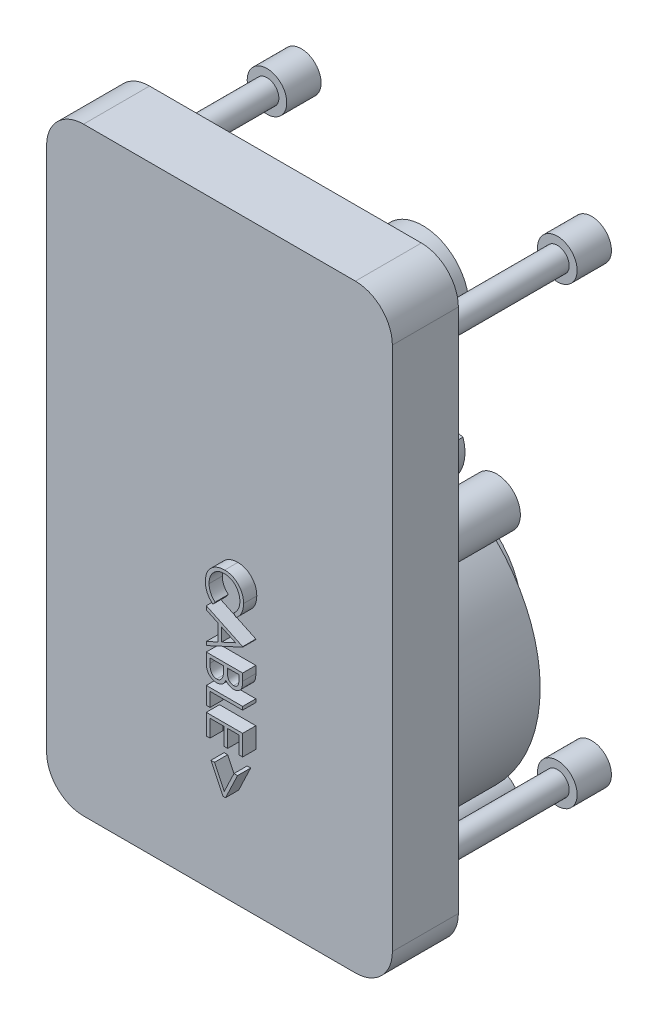
SolidWorks part; units mm, degrees
ref_plane "Front Plane" through (0, 0, 0) normal (0, 0, 1) x (1, 0, 0)
ref_plane "Top Plane" through (0, 0, 0) normal (0, 1, 0) x (1, 0, 0)
ref_plane "Right Plane" through (0, 0, 0) normal (1, 0, 0) x (0, 0, -1)
sketch "Sketch1" plane through (0, 0, 0) normal (0, 0, 1) x (1, 0, 0)
  line L0 (-13.081, 28.829) -> (13.081, 28.829)
  line L1 (-16.637, 25.273) -> (-16.637, -25.273)
  line L2 (-13.081, -28.829) -> (13.081, -28.829)
  line L3 (16.637, 25.273) -> (16.637, -25.273)
  line L4 (-16.637, 28.829) -> (16.637, -28.829) construction
  line L5 (-16.637, -28.829) -> (16.637, 28.829) construction
  line L6 (0, 36.9388) -> (0, -36.9388) construction
  line L7 (-21.0275, 0) -> (21.0275, 0) construction
  arc A0 (16.637, -25.273) -> (13.081, -28.829) centre (13.081, -25.273) cw
  arc A1 (-13.081, -28.829) -> (-16.637, -25.273) centre (-13.081, -25.273) cw
  arc A2 (16.637, 25.273) -> (13.081, 28.829) centre (13.081, 25.273) ccw
  arc A3 (-13.081, 28.829) -> (-16.637, 25.273) centre (-13.081, 25.273) ccw
  circle A4 centre (0, -12.7) radius 7.239
  circle A5 centre (0, 12.7) radius 4.445
  circle A6 centre (0, 14.605) radius 6.35
  circle A7 centre (0, -12.7) radius 14.351
  arc A8 (-3.6204, 1.1868) -> (3.6204, 1.1868) centre (0, 0) ccw
  circle A9 centre (13.97, 21.844) radius 1.016
  circle A10 centre (-13.97, 21.844) radius 1.016
  circle A11 centre (13.97, -21.844) radius 1.016
  circle A12 centre (-13.97, -21.844) radius 1.016
  arc A13 (6.6635, 0.0102) -> (10.0641, -2.4694) centre (8.89, -0.508) cw
  arc A14 (-10.0641, -2.4694) -> (-6.6635, 0.0102) centre (-8.89, -0.508) cw
  arc A15 (-10.0641, -22.9306) -> (-6.6635, -25.4102) centre (-8.89, -24.892) ccw
  arc A16 (6.6635, -25.4102) -> (10.0641, -22.9306) centre (8.89, -24.892) ccw
  point P0 (0, 0)
  dimension "D3" = 3.556
  dimension "D4" = 14.478
  dimension "D5" = 8.89
  dimension "D6" = 12.7
  dimension "D8" = 7.62
  dimension "D10" = 2.032
  dimension "D12" = 28.702
  dimension "D13" = 2.286
  dimension "D1" = 33.274
  dimension "D2" = 57.658
  dimension "D7" = 12.7
  dimension "D9" = 21.844
  dimension "D11" = 13.97
  dimension "D14" = 8.89
  dimension "D15" = 0.508
  dimension "D16" = 0.508
  dimension "D17" = 8.89
  dimension "D18" = 24.892
  dimension "D19" = 24.892
  dimension "D20" = 8.89
  dimension "D21" = 8.89
extrude "Boss-Extrude1" add sketch "Sketch1" against normal blind 10.16 contours A8 A7 A4 | A14 A7 | A7 A8 | A13 A7 | A7 A16 | A7 A15 | A4
sketch "Sketch2" plane through (0, 0, 0) normal (0, 0, 1) x (1, 0, 0)
  line L0 (-13.081, 28.829) -> (13.081, 28.829)
  line L1 (-16.637, 25.273) -> (-16.637, -25.273)
  line L2 (-13.081, -28.829) -> (13.081, -28.829)
  line L3 (16.637, 25.273) -> (16.637, -25.273)
  line L4 (-16.637, 28.829) -> (16.637, -28.829) construction
  line L5 (-16.637, -28.829) -> (16.637, 28.829) construction
  line L6 (0, 38.9705) -> (0, -34.9071) construction
  line L7 (-9.8575, 0) -> (32.1974, 0) construction
  arc A0 (16.637, -25.273) -> (13.081, -28.829) centre (13.081, -25.273) cw
  arc A1 (-13.081, -28.829) -> (-16.637, -25.273) centre (-13.081, -25.273) cw
  arc A2 (16.637, 25.273) -> (13.081, 28.829) centre (13.081, 25.273) ccw
  arc A3 (-13.081, 28.829) -> (-16.637, 25.273) centre (-13.081, 25.273) ccw
  circle A4 centre (0, -12.7) radius 7.239
  circle A5 centre (0, 12.7) radius 4.445
  circle A6 centre (0, 14.605) radius 6.35
  circle A7 centre (0, -12.7) radius 14.351
  arc A8 (-3.6204, 1.1868) -> (3.6204, 1.1868) centre (0, 0) ccw
  circle A9 centre (13.97, 21.844) radius 1.016
  circle A10 centre (-13.97, 21.844) radius 1.016
  circle A11 centre (13.97, -21.844) radius 1.016
  circle A12 centre (-13.97, -21.844) radius 1.016
  arc A13 (6.6635, 0.0102) -> (10.0641, -2.4694) centre (8.89, -0.508) cw
  arc A14 (-10.0641, -2.4694) -> (-6.6635, 0.0102) centre (-8.89, -0.508) cw
  arc A15 (-10.0641, -22.9306) -> (-6.6635, -25.4102) centre (-8.89, -24.892) ccw
  arc A16 (6.6635, -25.4102) -> (10.0641, -22.9306) centre (8.89, -24.892) ccw
  point P0 (0, 0)
  dimension "D3" = 3.556
  dimension "D4" = 14.478
  dimension "D5" = 8.89
  dimension "D6" = 12.7
  dimension "D8" = 7.62
  dimension "D10" = 2.032
  dimension "D12" = 28.702
  dimension "D13" = 2.286
  dimension "D1" = 33.274
  dimension "D2" = 57.658
  dimension "D7" = 12.7
  dimension "D9" = 21.844
  dimension "D11" = 13.97
  dimension "D14" = 8.89
  dimension "D15" = 0.508
  dimension "D16" = 0.508
  dimension "D17" = 8.89
  dimension "D18" = 24.892
  dimension "D19" = 24.892
  dimension "D20" = 8.89
  dimension "D21" = 8.89
extrude "Boss-Extrude2" add sketch "Sketch2" against normal blind 1.778 separate body contours A5 | A5 A6
sketch "Sketch3" plane through (0, 0, -10.16) normal (0, 0, -1) x (-1, 0, 0)
  circle A0 centre (-8.89, -0.508) radius 2.286
  circle A1 centre (8.89, -24.892) radius 2.286
  circle A2 centre (-8.89, -24.892) radius 2.286
  circle A3 centre (8.89, -0.508) radius 2.286
extrude "Boss-Extrude3" add sketch "Sketch3" along normal blind 1.27
sketch "Sketch4" plane through (0, 0, -10.16) normal (0, 0, -1) x (-1, 0, 0)
  line L0 (-13.081, 28.829) -> (13.081, 28.829)
  line L1 (-16.637, 25.273) -> (-16.637, -25.273)
  line L2 (-13.081, -28.829) -> (13.081, -28.829)
  line L3 (16.637, 25.273) -> (16.637, -25.273)
  line L4 (-16.637, 28.829) -> (16.637, -28.829) construction
  line L5 (-16.637, -28.829) -> (16.637, 28.829) construction
  line L6 (0, 23.9866) -> (0, -49.891) construction
  line L7 (7.1619, 0) -> (49.2169, 0) construction
  arc A0 (16.637, -25.273) -> (13.081, -28.829) centre (13.081, -25.273) cw
  arc A1 (-13.081, -28.829) -> (-16.637, -25.273) centre (-13.081, -25.273) cw
  arc A2 (16.637, 25.273) -> (13.081, 28.829) centre (13.081, 25.273) ccw
  arc A3 (-13.081, 28.829) -> (-16.637, 25.273) centre (-13.081, 25.273) ccw
  circle A4 centre (0, -12.7) radius 7.239
  circle A5 centre (0, 12.7) radius 4.445
  circle A6 centre (0, 14.605) radius 6.35
  circle A7 centre (0, -12.7) radius 14.351
  arc A8 (-3.6204, 1.1868) -> (3.6204, 1.1868) centre (0, 0) ccw
  circle A9 centre (13.97, 21.844) radius 1.016
  circle A10 centre (-13.97, 21.844) radius 1.016
  circle A11 centre (13.97, -21.844) radius 1.016
  circle A12 centre (-13.97, -21.844) radius 1.016
  arc A13 (6.6635, 0.0102) -> (10.0641, -2.4694) centre (8.89, -0.508) cw
  arc A14 (-10.0641, -2.4694) -> (-6.6635, 0.0102) centre (-8.89, -0.508) cw
  arc A15 (-10.0641, -22.9306) -> (-6.6635, -25.4102) centre (-8.89, -24.892) ccw
  arc A16 (6.6635, -25.4102) -> (10.0641, -22.9306) centre (8.89, -24.892) ccw
  point P0 (0, 0)
  dimension "D3" = 3.556
  dimension "D4" = 14.478
  dimension "D5" = 8.89
  dimension "D6" = 12.7
  dimension "D8" = 7.62
  dimension "D10" = 2.032
  dimension "D12" = 28.702
  dimension "D13" = 2.286
  dimension "D1" = 33.274
  dimension "D2" = 57.658
  dimension "D7" = 12.7
  dimension "D9" = 21.844
  dimension "D11" = 13.97
  dimension "D14" = 8.89
  dimension "D15" = 0.508
  dimension "D16" = 0.508
  dimension "D17" = 8.89
  dimension "D18" = 24.892
  dimension "D19" = 24.892
  dimension "D20" = 8.89
  dimension "D21" = 8.89
extrude "Boss-Extrude4" add sketch "Sketch4" along normal blind 3.302 contours A7 A8
sketch "Sketch5" plane through (0, 0, -1.778) normal (0, 0, -1) x (-1, 0, 0)
  line L0 (-13.081, 28.829) -> (13.081, 28.829)
  line L1 (-16.637, 25.273) -> (-16.637, -25.273)
  line L2 (-13.081, -28.829) -> (13.081, -28.829)
  line L3 (16.637, 25.273) -> (16.637, -25.273)
  line L4 (-16.637, 28.829) -> (16.637, -28.829) construction
  line L5 (-16.637, -28.829) -> (16.637, 28.829) construction
  line L6 (0, 36.0331) -> (0, -37.8445) construction
  line L7 (26.8703, 0) -> (68.9252, 0) construction
  arc A0 (16.637, -25.273) -> (13.081, -28.829) centre (13.081, -25.273) cw
  arc A1 (-13.081, -28.829) -> (-16.637, -25.273) centre (-13.081, -25.273) cw
  arc A2 (16.637, 25.273) -> (13.081, 28.829) centre (13.081, 25.273) ccw
  arc A3 (-13.081, 28.829) -> (-16.637, 25.273) centre (-13.081, 25.273) ccw
  circle A4 centre (0, -12.7) radius 7.239
  circle A5 centre (0, 12.7) radius 4.445
  circle A6 centre (0, 14.605) radius 6.35
  circle A7 centre (0, -12.7) radius 14.351
  arc A8 (-3.6204, 1.1868) -> (3.6204, 1.1868) centre (0, 0) ccw
  circle A9 centre (13.97, 21.844) radius 1.016
  circle A10 centre (-13.97, 21.844) radius 1.016
  circle A11 centre (13.97, -21.844) radius 1.016
  circle A12 centre (-13.97, -21.844) radius 1.016
  arc A13 (6.6635, 0.0102) -> (10.0641, -2.4694) centre (8.89, -0.508) cw
  arc A14 (-10.0641, -2.4694) -> (-6.6635, 0.0102) centre (-8.89, -0.508) cw
  arc A15 (-10.0641, -22.9306) -> (-6.6635, -25.4102) centre (-8.89, -24.892) ccw
  arc A16 (6.6635, -25.4102) -> (10.0641, -22.9306) centre (8.89, -24.892) ccw
  point P0 (0, 0)
  dimension "D3" = 3.556
  dimension "D4" = 14.478
  dimension "D5" = 8.89
  dimension "D6" = 12.7
  dimension "D8" = 7.62
  dimension "D10" = 2.032
  dimension "D12" = 28.702
  dimension "D13" = 2.286
  dimension "D1" = 33.274
  dimension "D2" = 57.658
  dimension "D7" = 12.7
  dimension "D9" = 21.844
  dimension "D11" = 13.97
  dimension "D14" = 8.89
  dimension "D15" = 0.508
  dimension "D16" = 0.508
  dimension "D17" = 8.89
  dimension "D18" = 24.892
  dimension "D19" = 24.892
  dimension "D20" = 8.89
  dimension "D21" = 8.89
extrude "Boss-Extrude5" add sketch "Sketch5" along normal blind 11.43 contours A5
sketch "Sketch6" plane through (0, 0, 0) normal (0, 0, 1) x (1, 0, 0)
  line L0 (-13.081, 28.829) -> (13.081, 28.829)
  line L1 (-16.637, 25.273) -> (-16.637, -25.273)
  line L2 (-13.081, -28.829) -> (13.081, -28.829)
  line L3 (16.637, 25.273) -> (16.637, -25.273)
  line L4 (-16.637, 28.829) -> (16.637, -28.829) construction
  line L5 (-16.637, -28.829) -> (16.637, 28.829) construction
  line L6 (0, 36.0885) -> (0, -37.789) construction
  line L7 (-47.9194, 0) -> (-5.8644, 0) construction
  arc A0 (16.637, -25.273) -> (13.081, -28.829) centre (13.081, -25.273) cw
  arc A1 (-13.081, -28.829) -> (-16.637, -25.273) centre (-13.081, -25.273) cw
  arc A2 (16.637, 25.273) -> (13.081, 28.829) centre (13.081, 25.273) ccw
  arc A3 (-13.081, 28.829) -> (-16.637, 25.273) centre (-13.081, 25.273) ccw
  circle A4 centre (0, -12.7) radius 7.239
  circle A5 centre (0, 12.7) radius 4.445
  circle A6 centre (0, 14.605) radius 6.35
  circle A7 centre (0, -12.7) radius 14.351
  arc A8 (-3.6204, 1.1868) -> (3.6204, 1.1868) centre (0, 0) ccw
  circle A9 centre (13.97, 21.844) radius 1.143
  circle A10 centre (-13.97, 21.844) radius 1.143
  circle A11 centre (13.97, -21.844) radius 1.143
  circle A12 centre (-13.97, -21.844) radius 1.143
  arc A13 (6.6635, 0.0102) -> (10.0641, -2.4694) centre (8.89, -0.508) cw
  arc A14 (-10.0641, -2.4694) -> (-6.6635, 0.0102) centre (-8.89, -0.508) cw
  arc A15 (-10.0641, -22.9306) -> (-6.6635, -25.4102) centre (-8.89, -24.892) ccw
  arc A16 (6.6635, -25.4102) -> (10.0641, -22.9306) centre (8.89, -24.892) ccw
  point P0 (0, 0)
  dimension "D3" = 3.556
  dimension "D4" = 14.478
  dimension "D5" = 8.89
  dimension "D6" = 12.7
  dimension "D8" = 7.62
  dimension "D10" = 2.286
  dimension "D12" = 28.702
  dimension "D13" = 2.286
  dimension "D1" = 33.274
  dimension "D2" = 57.658
  dimension "D7" = 12.7
  dimension "D9" = 21.844
  dimension "D11" = 13.97
  dimension "D14" = 8.89
  dimension "D15" = 0.508
  dimension "D16" = 0.508
  dimension "D17" = 8.89
  dimension "D18" = 24.892
  dimension "D19" = 24.892
  dimension "D20" = 8.89
  dimension "D21" = 8.89
extrude "Boss-Extrude6" add sketch "Sketch6" against normal blind 15.494 separate body contours A10 | A9 | A12 | A11
sketch "Sketch7" plane through (0, 0, -10.16) normal (0, 0, -1) x (-1, 0, 0)
  line L0 (-13.081, 28.829) -> (13.081, 28.829)
  line L1 (-16.637, 25.273) -> (-16.637, -25.273)
  line L2 (-13.081, -28.829) -> (13.081, -28.829)
  line L3 (16.637, 25.273) -> (16.637, -25.273)
  line L4 (-16.637, 28.829) -> (16.637, -28.829) construction
  line L5 (-16.637, -28.829) -> (16.637, 28.829) construction
  line L6 (0, 26.9541) -> (0, -46.9235) construction
  line L7 (8.0915, 0) -> (50.1464, 0) construction
  arc A0 (16.637, -25.273) -> (13.081, -28.829) centre (13.081, -25.273) cw
  arc A1 (-13.081, -28.829) -> (-16.637, -25.273) centre (-13.081, -25.273) cw
  arc A2 (16.637, 25.273) -> (13.081, 28.829) centre (13.081, 25.273) ccw
  arc A3 (-13.081, 28.829) -> (-16.637, 25.273) centre (-13.081, 25.273) ccw
  circle A4 centre (0, -12.7) radius 7.239
  circle A5 centre (0, 12.7) radius 4.445
  circle A6 centre (0, 14.605) radius 6.35
  circle A7 centre (0, -12.7) radius 14.351
  arc A8 (-3.6204, 1.1868) -> (3.6204, 1.1868) centre (0, 0) ccw
  circle A9 centre (13.97, 21.844) radius 1.016
  circle A10 centre (-13.97, 21.844) radius 1.016
  circle A11 centre (13.97, -21.844) radius 1.016
  circle A12 centre (-13.97, -21.844) radius 1.016
  arc A13 (6.6635, 0.0102) -> (10.0641, -2.4694) centre (8.89, -0.508) cw
  arc A14 (-10.0641, -2.4694) -> (-6.6635, 0.0102) centre (-8.89, -0.508) cw
  arc A15 (-10.0641, -22.9306) -> (-6.6635, -25.4102) centre (-8.89, -24.892) ccw
  arc A16 (6.6635, -25.4102) -> (10.0641, -22.9306) centre (8.89, -24.892) ccw
  point P0 (0, 0)
  dimension "D3" = 3.556
  dimension "D4" = 14.478
  dimension "D5" = 8.89
  dimension "D6" = 12.7
  dimension "D8" = 7.62
  dimension "D10" = 2.032
  dimension "D12" = 28.702
  dimension "D13" = 2.286
  dimension "D1" = 33.274
  dimension "D2" = 57.658
  dimension "D7" = 12.7
  dimension "D9" = 21.844
  dimension "D11" = 13.97
  dimension "D14" = 8.89
  dimension "D15" = 0.508
  dimension "D16" = 0.508
  dimension "D17" = 8.89
  dimension "D18" = 24.892
  dimension "D19" = 24.892
  dimension "D20" = 8.89
  dimension "D21" = 8.89
extrude "Boss-Extrude7" add sketch "Sketch7" along normal blind 5.334 contours A4
sketch "Sketch8" plane through (0, 0, 0) normal (0, 0, 1) x (1, 0, 0)
  line L1 (-13.081, 28.829) -> (13.081, 28.829)
  line L2 (-16.637, 25.273) -> (-16.637, -25.273)
  line L3 (-13.081, -28.829) -> (13.081, -28.829)
  line L4 (16.637, 25.273) -> (16.637, -25.273)
  line L5 (-16.637, 28.829) -> (16.637, -28.829) construction
  line L6 (-16.637, -28.829) -> (16.637, 28.829) construction
  arc A8 (16.637, -25.273) -> (13.081, -28.829) centre (13.081, -25.273) cw
  arc A13 (-13.081, -28.829) -> (-16.637, -25.273) centre (-13.081, -25.273) cw
  arc A14 (16.637, 25.273) -> (13.081, 28.829) centre (13.081, 25.273) ccw
  arc A15 (-13.081, 28.829) -> (-16.637, 25.273) centre (-13.081, 25.273) ccw
  point P0 (0, 0)
  dimension "D3" = 3.556
  dimension "D1" = 33.274
  dimension "D23" = 57.658
extrude "Boss-Extrude8" add sketch "Sketch8" along normal blind 6.35
sketch "Sketch9" plane through (0, 0, -15.494) normal (0, 0, -1) x (-1, 0, 0)
  circle A0 centre (-13.97, 21.844) radius 1.905
  circle A1 centre (13.97, 21.844) radius 1.905
  circle A2 centre (13.97, -21.844) radius 1.905
  circle A3 centre (-13.97, -21.844) radius 1.905
  dimension "D1" = 3.81
extrude "Boss-Extrude9" add sketch "Sketch9" against normal blind 3.302
sketch "Sketch10" plane through (0, 0, 6.35) normal (0, 0, 1) x (1, 0, 0)
  line L0 (0, 0) -> (0, -28.829) construction
  line L1 (-13.081, -28.829) -> (13.081, -28.829) construction
  text T0 "CABLE >"
extrude "Boss-Extrude10" add sketch "Sketch10" along normal blind 1.27
